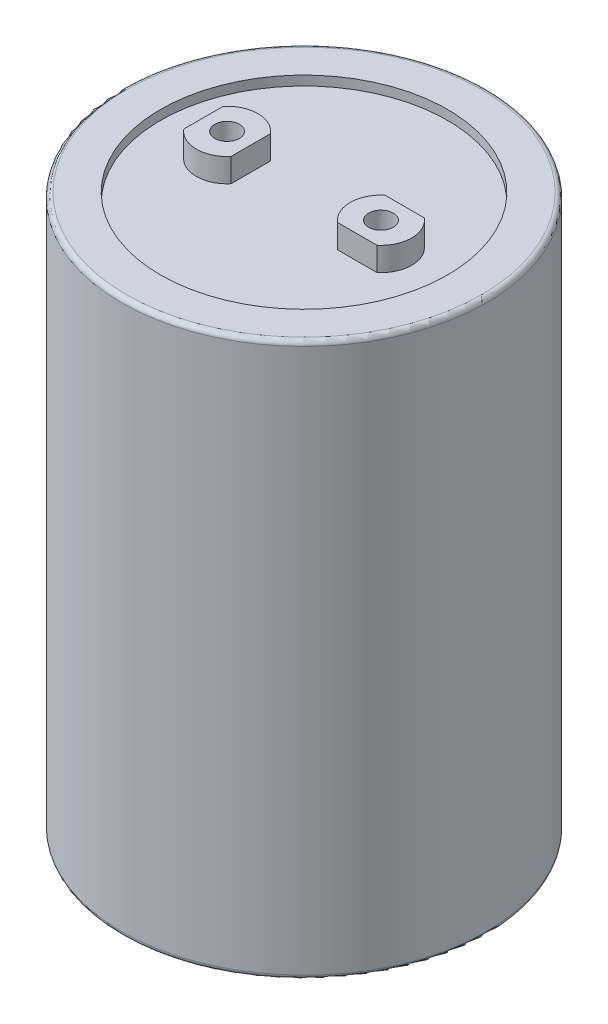
SolidWorks part; units mm, degrees
ref_plane "Front Plane" through (0, 0, 0) normal (0, 0, 1) x (1, 0, 0)
ref_plane "Top Plane" through (0, 0, 0) normal (0, 1, 0) x (1, 0, 0)
ref_plane "Right Plane" through (0, 0, 0) normal (1, 0, 0) x (0, 0, -1)
sketch "Sketch1" plane through (0, 0, 0) normal (0, 1, 0) x (1, 0, 0)
  circle A0 centre (0, 0) radius 38.5
  dimension "D1" = 77
extrude "Boss-Extrude1" add sketch "Sketch1" along normal blind 115
sketch "Sketch2" plane through (0, 115, 0) normal (0, 1, 0) x (1, 0, 0)
  line L0 (-38.5, 0) -> (38.5, 0) construction
  line L1 (0, 0) -> (0, 38.5) construction
  line L2 (-16.25, 0) -> (-16.25, 6.5) construction
  line L3 (-11.25, 4.1533) -> (-11.25, -4.1533) construction
  line L4 (-21.25, -4.1533) -> (-21.25, 4.1533) construction
  line L5 (12.0967, 5) -> (20.4033, 5) construction
  line L6 (20.4033, -5) -> (12.0967, -5) construction
  line L7 (-21.25, 4.1533) -> (-21.25, -4.1533)
  line L8 (-11.25, -4.1533) -> (-11.25, 4.1533)
  line L9 (12.0967, 5) -> (20.4033, 5)
  line L10 (20.4033, -5) -> (12.0967, -5)
  circle A0 centre (0, 0) radius 38.5 construction
  circle A1 centre (16.25, 0) radius 6.5 construction
  circle A2 centre (-16.25, 0) radius 6.5 construction
  arc A3 (-11.25, 4.1533) -> (-21.25, 4.1533) centre (-16.25, 0) ccw
  arc A4 (-11.25, -4.1533) -> (-21.25, -4.1533) centre (-16.25, 0) cw
  arc A5 (12.0967, 5) -> (12.0967, -5) centre (16.25, 0) ccw
  arc A6 (20.4033, 5) -> (20.4033, -5) centre (16.25, 0) cw
  circle A7 centre (-16.25, 0) radius 2.6
  circle A8 centre (16.25, 0) radius 2.6
  dimension "D1" = 13
  dimension "D2" = 13
  dimension "D6" = 5.2
  dimension "D3" = 32.5
  dimension "D4" = 10
  dimension "D5" = 10
extrude "Boss-Extrude2" add sketch "Sketch2" along normal blind 5
sketch "Sketch3" plane through (0, 115, 0) normal (0, 1, 0) x (1, 0, 0)
  circle A0 centre (0, 0) radius 38.5
  circle A1 centre (0, 0) radius 30.3
  circle A2 centre (0, 0) radius 38.5 construction
  dimension "D1" = 8.2
extrude "Boss-Extrude3" add sketch "Sketch3" along normal blind 2
fillet "Fillet1" radius 1 2 edges at (0, 0, 38.5) (0, 117, 38.5)
sketch "Esquisse1" plane through (0, 0, 0) normal (0, -1, 0) x (1, 0, 0)
  circle A0 centre (0, 0) radius 6
  dimension "D1" = 12
extrude "Boss.-Extru.1" add sketch "Esquisse1" along normal blind 16
